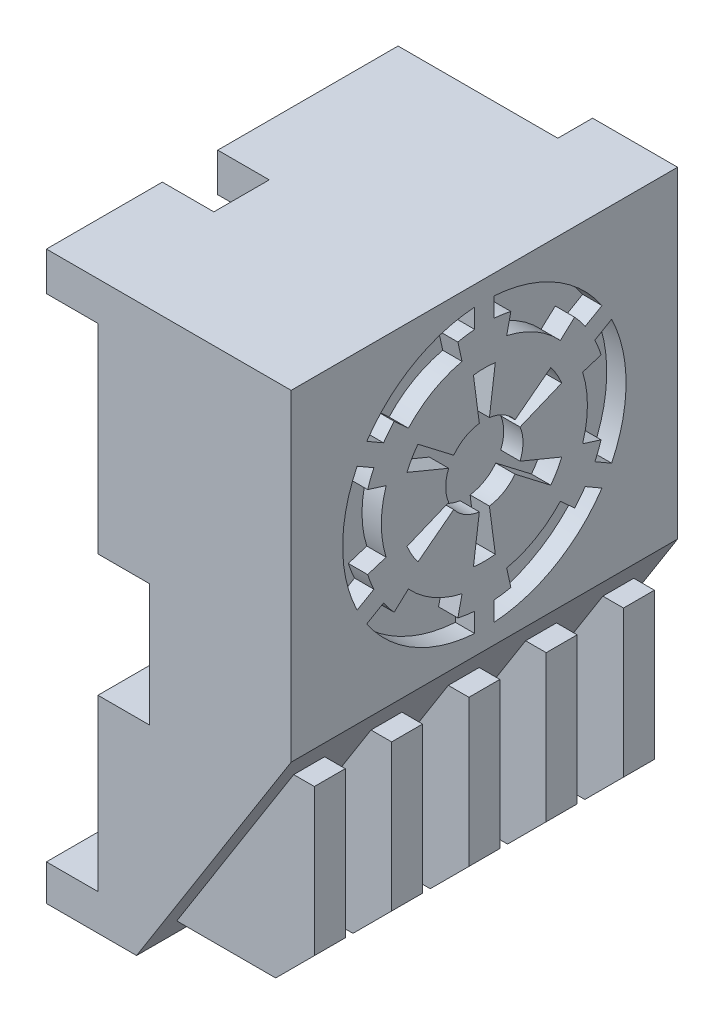
SolidWorks part; units mm, degrees
material "PE Low/Medium Density"
ref_plane "Front Plane" through (0, 0, 0) normal (0, 0, 1) x (1, 0, 0)
ref_plane "Top Plane" through (0, 0, 0) normal (0, 1, 0) x (1, 0, 0)
ref_plane "Right Plane" through (0, 0, 0) normal (1, 0, 0) x (0, 0, -1)
sketch "Sketch1" plane through (0, 0, 0) normal (1, 0, 0) x (0, 0, -1)
  line L2 (-15, -12.5) -> (15, -12.5)
  line L3 (-15, -12.5) -> (-15, 12.5)
  line L4 (-15, 12.5) -> (15, 12.5)
  line L5 (15, -12.5) -> (15, 12.5)
  line L6 (-15, -12.5) -> (15, 12.5) construction
  line L7 (-15, 12.5) -> (15, -12.5) construction
  point P1 (0, 0)
  dimension "D1" = 30
  dimension "D2" = 25
extrude "Boss-Extrude1" add sketch "Sketch1" along normal blind 3
sketch "Sketch2" plane through (0, 0, 0) normal (-1, 0, 0) x (0, 0, 1)
  line L0 (6, 9.5) -> (1.7, 9.5) construction
  line L1 (15, 12.5) -> (6, 12.5)
  line L2 (15, 12.5) -> (15, 9.5)
  line L3 (15, 9.5) -> (6, 9.5)
  line L4 (6, 12.5) -> (6, 9.5)
  line L5 (-15, 12.5) -> (15, 12.5) construction
  line L6 (1.7, 9.5) -> (-12.3, 9.5)
  line L7 (1.7, 9.5) -> (1.7, 12.5)
  line L8 (1.7, 12.5) -> (-12.3, 12.5)
  line L9 (-12.3, 9.5) -> (-12.3, 12.5)
  dimension "D1" = 9
  dimension "D2" = 3
  dimension "D3" = 4.3
  dimension "D4" = 14
extrude "Boss-Extrude2" add sketch "Sketch2" along normal blind 16
sketch "Sketch3" plane through (0, 0, 0) normal (-1, 0, 0) x (0, 0, 1)
  line L1 (1.7, 12.5) -> (6, 12.5)
  line L2 (1.7, 12.5) -> (1.7, 9.5)
  line L3 (1.7, 9.5) -> (6, 9.5)
  line L4 (6, 12.5) -> (6, 9.5)
extrude "Boss-Extrude3" add sketch "Sketch3" along normal blind 12
sketch "Sketch4" plane through (0, 0, 0) normal (-1, 0, 0) x (0, 0, 1)
  line L0 (15, 9.5) -> (15, -7) construction
  line L1 (15, 9.5) -> (15, -12.5) construction
  line L3 (15, -7) -> (-15, -7)
  line L4 (15, -7) -> (15, -12.5)
  line L5 (15, -12.5) -> (-15, -12.5)
  line L6 (-15, -7) -> (-15, -12.5)
  dimension "D1" = 16.5
extrude "Boss-Extrude4" add sketch "Sketch4" along normal blind 8
sketch "Sketch5" plane through (0, 0, 15) normal (0, 0, 1) x (1, 0, 0)
  line L0 (-8, -12.5) -> (-8, -31.5) construction
  line L1 (-12, -31.5) -> (-9, -31.5)
  line L2 (-9, -31.5) -> (3, -12.5)
  line L3 (3, -12.5) -> (-8, -12.5)
  line L4 (-8, -12.5) -> (-8, -15.5)
  line L5 (-8, -15.5) -> (-12, -15.5)
  line L6 (-12, -15.5) -> (-12, -31.5)
  line L7 (-9, -31.5) -> (-8, -31.5) construction
  dimension "D1" = 24.5
  dimension "D2" = 3
  dimension "D3" = 4
  dimension "D4" = 8.5
extrude "Boss-Extrude5" add sketch "Sketch5" against normal up to surface (30 mm away) up to face at (-1.6667, -2.3333, -15)
sketch "Sketch7" plane through (0, -31.5, 0) normal (0, -1, 0) x (1, 0, 0)
  line L0 (-9, -15) -> (-12, -15) construction
  line L1 (-12, 15) -> (-16, 15)
  line L2 (-12, 15) -> (-12, 6)
  line L3 (-12, 6) -> (-16, 6)
  line L4 (-16, 15) -> (-16, 6)
  line L5 (-12, 1.7) -> (-16, 1.7)
  line L6 (-12, 1.7) -> (-12, -15)
  line L7 (-12, -15) -> (-16, -15)
  line L8 (-16, 1.7) -> (-16, -15)
  line L9 (-16, -12.3) -> (-16, 1.7) construction
extrude "Boss-Extrude6" add sketch "Sketch7" against normal blind 3
sketch "Sketch9" plane through (0, 0, 15) normal (0, 0, 1) x (1, 0, 0)
  line L2 (0, -7) -> (-12, -7)
  line L3 (0, -7) -> (0, 9.5)
  line L4 (0, 9.5) -> (-12, 9.5)
  line L5 (-12, -7) -> (-12, 9.5)
extrude "Boss-Extrude7" add sketch "Sketch9" against normal blind 2
sketch "Sketch10" plane through (7.7881, -4.9188, 0) normal (0.8455, -0.534, 0) x (0, 0, -1)
  line L0 (-7.2, -11.9666) -> (-7.2, -28.9666)
  line L1 (-13.2, -11.9666) -> (-10.8, -11.9666)
  line L2 (-13.2, -11.9666) -> (-13.2, -28.9666)
  line L3 (-13.2, -28.9666) -> (-10.8, -28.9666)
  line L4 (-10.8, -11.9666) -> (-10.8, -28.9666)
  line L5 (-7.2, -11.9666) -> (-4.8, -11.9666)
  line L6 (-4.8, -11.9666) -> (-4.8, -28.9666)
  line L7 (-7.2, -28.9666) -> (-4.8, -28.9666)
  line L8 (-1.2, -11.9666) -> (-1.2, -28.9666)
  line L9 (-1.2, -11.9666) -> (1.2, -11.9666)
  line L10 (1.2, -11.9666) -> (1.2, -28.9666)
  line L11 (-1.2, -28.9666) -> (1.2, -28.9666)
  line L12 (4.8, -11.9666) -> (4.8, -28.9666)
  line L13 (4.8, -11.9666) -> (7.2, -11.9666)
  line L14 (7.2, -11.9666) -> (7.2, -28.9666)
  line L15 (4.8, -28.9666) -> (7.2, -28.9666)
  line L16 (10.8, -11.9666) -> (10.8, -28.9666)
  line L17 (10.8, -11.9666) -> (13.2, -11.9666)
  line L18 (13.2, -11.9666) -> (13.2, -28.9666)
  line L19 (10.8, -28.9666) -> (13.2, -28.9666)
  line L20 (-15, -31.4388) -> (-15, -8.9666) construction
  line L25 (-15, -8.9666) -> (15, -8.9666) construction
  dimension "D1" = 5
  dimension "D2" = 2.4
  dimension "D3" = 1.8
  dimension "D4" = 17
  dimension "D5" = 3
sketch "Sketch11" plane through (3, 0, 0) normal (1, 0, 0) x (0, 0, -1)
  line L0 (-13.2, -15.0365) -> (-13.2, -29.4098) construction
  line L1 (-13.2, -29.4098) -> (-10.8, -29.4098) construction
  line L2 (-10.8, -15.0365) -> (-10.8, -29.4098) construction
  line L3 (-13.2, -15.0365) -> (-10.8, -15.0365) construction
  line L4 (-7.2, -15.0365) -> (-7.2, -29.4098) construction
  line L5 (-7.2, -29.4098) -> (-4.8, -29.4098) construction
  line L6 (-4.8, -15.0365) -> (-4.8, -29.4098) construction
  line L7 (-7.2, -15.0365) -> (-4.8, -15.0365) construction
  line L8 (-1.2, -15.0365) -> (-1.2, -29.4098) construction
  line L9 (-1.2, -29.4098) -> (1.2, -29.4098) construction
  line L10 (1.2, -15.0365) -> (1.2, -29.4098) construction
  line L11 (-1.2, -15.0365) -> (1.2, -15.0365) construction
  line L12 (4.8, -15.0365) -> (4.8, -29.4098) construction
  line L13 (4.8, -29.4098) -> (7.2, -29.4098) construction
  line L14 (7.2, -15.0365) -> (7.2, -29.4098) construction
  line L15 (4.8, -15.0365) -> (7.2, -15.0365) construction
  line L16 (10.8, -15.0365) -> (10.8, -29.4098) construction
  line L17 (10.8, -29.4098) -> (13.2, -29.4098) construction
  line L18 (13.2, -15.0365) -> (13.2, -29.4098) construction
  line L19 (10.8, -15.0365) -> (13.2, -15.0365) construction
  line L20 (-13.2, -15.0365) -> (-13.2, -29.4098)
  line L21 (-13.2, -29.4098) -> (-10.8, -29.4098)
  line L22 (-10.8, -15.0365) -> (-10.8, -29.4098)
  line L23 (-13.2, -15.0365) -> (-10.8, -15.0365)
  line L24 (-7.2, -15.0365) -> (-7.2, -29.4098)
  line L25 (-7.2, -29.4098) -> (-4.8, -29.4098)
  line L26 (-4.8, -15.0365) -> (-4.8, -29.4098)
  line L27 (-7.2, -15.0365) -> (-4.8, -15.0365)
  line L28 (-1.2, -15.0365) -> (-1.2, -29.4098)
  line L29 (-1.2, -29.4098) -> (1.2, -29.4098)
  line L30 (1.2, -15.0365) -> (1.2, -29.4098)
  line L31 (-1.2, -15.0365) -> (1.2, -15.0365)
  line L32 (4.8, -15.0365) -> (4.8, -29.4098)
  line L33 (4.8, -29.4098) -> (7.2, -29.4098)
  line L34 (7.2, -15.0365) -> (7.2, -29.4098)
  line L35 (4.8, -15.0365) -> (7.2, -15.0365)
  line L36 (10.8, -15.0365) -> (10.8, -29.4098)
  line L37 (10.8, -29.4098) -> (13.2, -29.4098)
  line L38 (13.2, -15.0365) -> (13.2, -29.4098)
  line L39 (10.8, -15.0365) -> (13.2, -15.0365)
extrude "Boss-Extrude8" add sketch "Sketch11" against normal up to surface (1.602 mm away)
chamfer "Chamfer1" distance 3 angle 45 5 edges at (3, -29.4098, -12) (3, -29.4098, -6) (3, -29.4098, 0) (3, -29.4098, 6) (3, -29.4098, 12)
sketch "Sketch12" plane through (3, 0, 0) normal (1, 0, 0) x (0, 0, -1)
  line L0 (0, 0) -> (0, 11) construction
  line L1 (-0.75, 10.9744) -> (-0.75, 9.4703)
  line L2 (0.75, 10.9744) -> (0.75, 9.4703)
  line L3 (-0.75, 9.4703) -> (0, 11) construction
  line L4 (0, 11) -> (0.75, 9.4703) construction
  line L5 (0, 0) -> (-3.5236, 15.8941) construction
  line L6 (0, 0) -> (3.5236, 15.8941) construction
  line L7 (3.5236, 15.8941) -> (0, 11) construction
  line L8 (0, 11) -> (-3.5236, 15.8941) construction
  line L9 (-3.5236, 15.8941) -> (3.5236, 15.8941) construction
  line L10 (-1.7315, 7.8104) -> (-2.0562, 9.2748)
  line L11 (1.7315, 7.8104) -> (2.0562, 9.2748)
  line L12 (0, 0) -> (-0.8484, 6.4444) construction
  line L13 (-0.8484, 6.4444) -> (0.8484, 6.4444) construction
  line L14 (0.8484, 6.4444) -> (0, 0) construction
  line L15 (-0.8484, 6.4444) -> (-0.3916, 2.9743)
  line L16 (0.8484, 6.4444) -> (0.3916, 2.9743)
  line L17 (9.1291, 6.1367) -> (7.8266, 5.3847)
  line L18 (9.8791, 4.8377) -> (8.5766, 4.0857)
  line L19 (5.8982, 5.4047) -> (7.0041, 6.4181)
  line L20 (7.6297, 2.4056) -> (9.0603, 2.8567)
  line L21 (5.1568, 3.9569) -> (2.3801, 1.8263)
  line L22 (6.0052, 2.4874) -> (2.7716, 1.1481)
  line L23 (9.8791, -4.8377) -> (8.5766, -4.0857)
  line L24 (9.1291, -6.1367) -> (7.8266, -5.3847)
  line L25 (7.6297, -2.4056) -> (9.0603, -2.8567)
  line L26 (5.8982, -5.4047) -> (7.0041, -6.4181)
  line L27 (6.0052, -2.4874) -> (2.7716, -1.1481)
  line L28 (5.1568, -3.9569) -> (2.3801, -1.8263)
  line L29 (0.75, -10.9744) -> (0.75, -9.4703)
  line L30 (-0.75, -10.9744) -> (-0.75, -9.4703)
  line L31 (1.7315, -7.8104) -> (2.0562, -9.2748)
  line L32 (-1.7315, -7.8104) -> (-2.0562, -9.2748)
  line L33 (0.8484, -6.4444) -> (0.3916, -2.9743)
  line L34 (-0.8484, -6.4444) -> (-0.3916, -2.9743)
  line L35 (-9.1291, -6.1367) -> (-7.8266, -5.3847)
  line L36 (-9.8791, -4.8377) -> (-8.5766, -4.0857)
  line L37 (-5.8982, -5.4047) -> (-7.0041, -6.4181)
  line L38 (-7.6297, -2.4056) -> (-9.0603, -2.8567)
  line L39 (-5.1568, -3.9569) -> (-2.3801, -1.8263)
  line L40 (-6.0052, -2.4874) -> (-2.7716, -1.1481)
  line L41 (-9.8791, 4.8377) -> (-8.5766, 4.0857)
  line L42 (-9.1291, 6.1367) -> (-7.8266, 5.3847)
  line L43 (-7.6297, 2.4056) -> (-9.0603, 2.8567)
  line L44 (-5.8982, 5.4047) -> (-7.0041, 6.4181)
  line L45 (-6.0052, 2.4874) -> (-2.7716, 1.1481)
  line L46 (-5.1568, 3.9569) -> (-2.3801, 1.8263)
  circle A0 centre (0, 0) radius 11
  circle A1 centre (0, 0) radius 9.5
  circle A2 centre (0, 0) radius 8
  circle A3 centre (0, 0) radius 6.5
  circle A4 centre (0, 0) radius 3
  point P0 (0, 6.4444)
  point P89 (0, 0)
  dimension "D1" = 22
  dimension "D2" = 1.5
  dimension "D6" = 1.5
  dimension "D7" = 25
  dimension "D8" = 15
  dimension "D9" = 6
  dimension "D3" = 1.5
  dimension "D4" = 1.5
  dimension "D5" = 3.5
extrude "Cut-Extrude1" cut sketch "Sketch12" against normal blind 1.5 contours A1 L1 A0 L42 | A1 L41 A0 L36 | A1 L35 A0 L30 | A1 L29 A0 L24 | A1 L23 A0 L18 | A1 L17 A0 L2 | A2 L10 A1 L44 | A2 L43 A1 L38 | A2 L37 A1 L32 | A2 L31 A1 L26 | A2 L25 A1 L20 | A2 L19 A1 L11 | A4 L46 A3 L45 | A4 L40 A3 L39 | A4 L34 A3 L33 | A4 L28 A3 L27 | A4 L22 A3 L21 | A4 L16 A3 L15 | A4
sketch "Sketch13" plane through (0, 0, 0) normal (-1, 0, 0) x (0, 0, 1)
  line L0 (13, -7) -> (-15, -7) construction
  line L1 (-15, 12.5) -> (-12.3, 12.5)
  line L2 (-15, 12.5) -> (-15, -7)
  line L3 (-15, -7) -> (-12.3, -7)
  line L4 (-12.3, 12.5) -> (-12.3, -7)
extrude "Boss-Extrude9" add sketch "Sketch13" along normal blind 3.6
sketch "Sketch14" plane through (0, 0, 15) normal (0, 0, 1) x (1, 0, 0)
  line L0 (-12, -28.5) -> (-16, -28.5) construction
  line L1 (-12, -7) -> (-8, -7)
  line L2 (-12, -7) -> (-12, -6)
  line L3 (-12, -6) -> (-8, -6)
  line L4 (-8, -7) -> (-8, -6)
  line L5 (-16, -28.5) -> (-12, -28.5)
  line L6 (-16, -28.5) -> (-16, -28.7)
  line L7 (-16, -28.7) -> (-12, -28.7)
  line L8 (-12, -28.5) -> (-12, -28.7)
  line L9 (-12, -15.5) -> (-12, -28.5) construction
  dimension "D1" = 1
  dimension "D2" = 0.2
extrude "Cut-Extrude2" cut sketch "Sketch14" against normal through all
